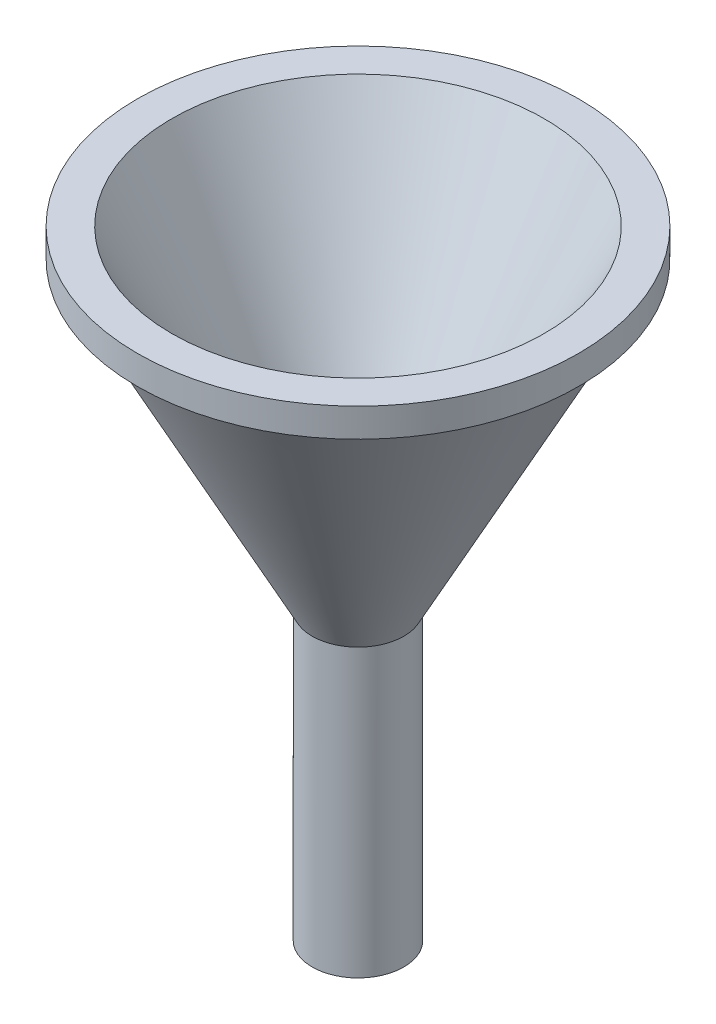
SolidWorks part; units mm, degrees
ref_plane "Front Plane" through (0, 0, 0) normal (0, 0, 1) x (1, 0, 0)
ref_plane "Top Plane" through (0, 0, 0) normal (0, 1, 0) x (1, 0, 0)
ref_plane "Right Plane" through (0, 0, 0) normal (1, 0, 0) x (0, 0, -1)
sketch "Sketch1" plane through (0, 0, 0) normal (0, 0, 1) x (1, 0, 0)
  line L0 (0, 0) -> (0, 136.7708) construction
  line L1 (2, 0) -> (2, 50)
  line L2 (2, 50) -> (32.5, 108)
  line L3 (32.5, 108) -> (38.5, 108)
  line L4 (38.5, 108) -> (8, 50)
  line L5 (8, 50) -> (8, 0)
  line L6 (8, 0) -> (2, 0)
  point P5 (0, 0)
  point P10 (8, -1.4939)
  point P11 (8, 8.6958)
  point P12 (8, 10.2747)
  point P13 (2, 0)
  point P14 (8, 2.2052)
  point P15 (2, 0)
  point P16 (8, 50.4465)
  point P17 (2, 0)
  point P18 (0, 0)
  point P19 (0, 0)
  dimension "D1" = 65
  dimension "D2" = 77
  dimension "D3" = 50
  dimension "D4" = 108
  dimension "D5" = 4
revolve "Revolve1" add sketch "Sketch1" angle 360 about L0
sketch "Sketch2" plane through (0, 108, 0) normal (0, 1, 0) x (1, 0, 0)
  circle A0 centre (0, 0) radius 38.5
  circle A1 centre (0, 0) radius 32.5
extrude "Boss-Extrude1" add sketch "Sketch2" against normal blind 5
